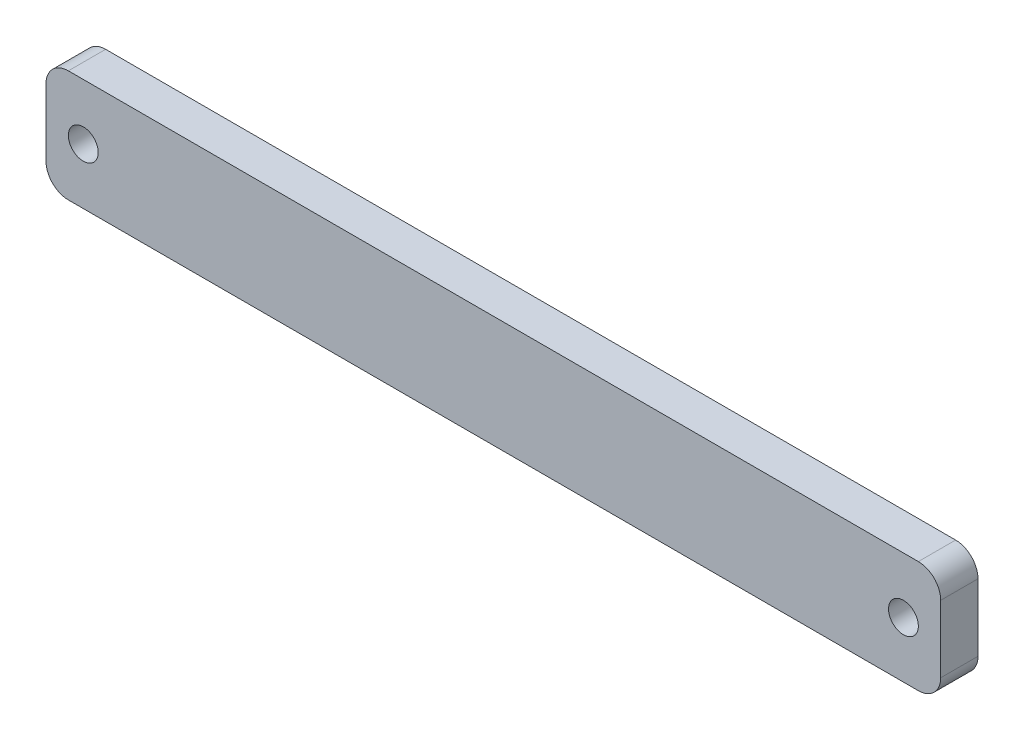
SolidWorks part; units mm, degrees
ref_plane "Plan de face" through (0, 0, 0) normal (0, 0, 1) x (1, 0, 0)
ref_plane "Plan de dessus" through (0, 0, 0) normal (0, 1, 0) x (1, 0, 0)
ref_plane "Plan de droite" through (0, 0, 0) normal (1, 0, 0) x (0, 0, -1)
sketch "Esquisse1" plane through (0, 0, 0) normal (0, 0, 1) x (1, 0, 0)
  line L0 (0, 13.4438) -> (0, -14.6044) construction
  line L1 (-60, 7.5) -> (60, 7.5)
  line L2 (-60, 7.5) -> (-60, -7.5)
  line L3 (-60, -7.5) -> (60, -7.5)
  line L4 (60, 7.5) -> (60, -7.5)
  line L5 (-60, 7.5) -> (60, -7.5) construction
  line L6 (-60, -7.5) -> (60, 7.5) construction
  circle A0 centre (-55, 0) radius 2
  circle A1 centre (55, 0) radius 2
  point P0 (0, 0)
  dimension "D3" = 4
  dimension "D1" = 120
  dimension "D2" = 15
  dimension "D4" = 5
  dimension "D5" = 7.5
extrude "Boss.-Extru.1" add sketch "Esquisse1" along normal blind 5
fillet "Congé1" radius 3 4 edges at (-60, -7.5, 2.5) (-60, 7.5, 2.5) (60, -7.5, 2.5) (60, 7.5, 2.5)
